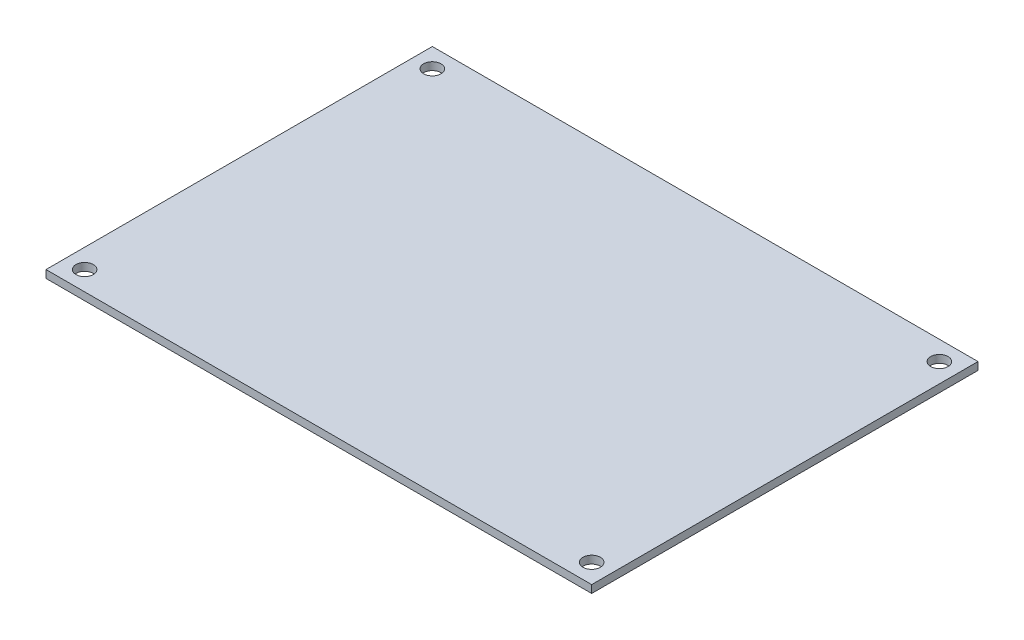
SolidWorks part; units mm, degrees
ref_plane "Front Plane" through (0, 0, 0) normal (0, 0, 1) x (1, 0, 0)
ref_plane "Top Plane" through (0, 0, 0) normal (0, 1, 0) x (1, 0, 0)
ref_plane "Right Plane" through (0, 0, 0) normal (1, 0, 0) x (0, 0, -1)
sketch "Sketch1" plane through (0, 0, 0) normal (0, 1, 0) x (1, 0, 0)
  line L1 (-56.5, 40) -> (56.5, 40)
  line L2 (-56.5, 40) -> (-56.5, -40)
  line L3 (-56.5, -40) -> (56.5, -40)
  line L4 (56.5, 40) -> (56.5, -40)
  line L5 (-56.5, 40) -> (56.5, -40) construction
  line L6 (-56.5, -40) -> (56.5, 40) construction
  point P0 (0, 0)
  dimension "D1" = 113
  dimension "D2" = 80
extrude "Boss-Extrude1" add sketch "Sketch1" along normal blind 1.6
hole_wizard "M3 Clearance Hole1" positions "Sketch2" profile "Sketch3" hole size "M3" standard "ANSI Metric" end condition through all
sketch "Sketch2" plane through (0, 1.6, 0) normal (0, 1, 0) x (1, 0, 0)
  line L0 (-56.5, 40) -> (-56.5, -40) construction
  line L1 (56.5, 40) -> (-56.5, 40) construction
  point P0 (-52.5, 36)
  dimension "D1" = 4
  dimension "D2" = 52.5
  dimension "D3" = 4
  dimension "D4" = 36
sketch "Sketch3" plane through (-52.5, 1.6, -36) normal (1, 0, 0) x (0, 0, 1)
  line L0 (0, 0) -> (0, 1.6)
  line L1 (0, 1.6) -> (1.8, 1.6)
  line L2 (1.8, 1.6) -> (1.8, 0)
  line L5 (1.8, 0) -> (0, 0)
  line L11 (0, -6.35) -> (0, 107.95) construction
  dimension "Thru Hole Dia." = 3.6
  dimension "Thru Hole Depth" = 1.6
mirror "Mirror1" about plane through (0, 0, 0) normal (1, 0, 0) of "M3 Clearance Hole1"
mirror "Mirror2" about plane through (0, 0, 0) normal (0, 0, 1) of "Mirror1", "M3 Clearance Hole1"
